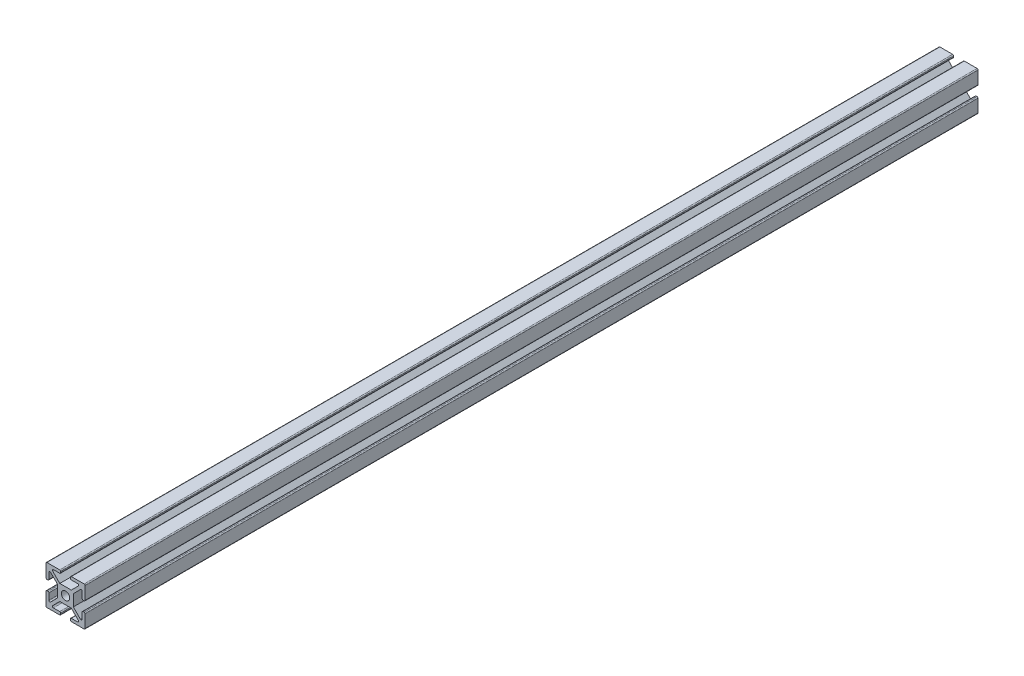
SolidWorks part; units mm, degrees
material "6061 Alloy"
ref_plane "Front Plane" through (0, 0, 0) normal (0, 0, 1) x (1, 0, 0)
ref_plane "Top Plane" through (0, 0, 0) normal (0, 1, 0) x (1, 0, 0)
ref_plane "Right Plane" through (0, 0, 0) normal (1, 0, 0) x (0, 0, -1)
sketch "Sketch1" plane through (0, 0, 0) normal (0, 0, 1) x (1, 0, 0)
  line L0 (-10, 2.5) -> (-8.5, 2.5)
  line L1 (-2.9393, 4) -> (0, 4)
  line L2 (-2.5, 10) -> (-10, 10)
  line L3 (-7.4393, 8.5) -> (-2.9393, 4)
  line L4 (-2.5, 8.5) -> (-7.4393, 8.5)
  line L5 (-8.5, 2.5) -> (-8.5, 7.4393)
  line L6 (-8.5, 7.4393) -> (-4, 2.9393)
  line L7 (-4, 2.9393) -> (-4, 0)
  line L8 (-4, 0) -> (-10, 0) construction
  line L9 (0, 10) -> (0, -10) construction
  line L10 (-10, 10) -> (0, 0) construction
  line L11 (-10, 2.5) -> (-10, 10)
  line L12 (-2.5, 10) -> (-2.5, 8.5)
  line L13 (-2.5, 10) -> (0, 10) construction
  line L14 (-10, 2.5) -> (-10, 0) construction
  line L15 (2.9393, 4) -> (0, 4)
  line L16 (4, 2.9393) -> (4, 0)
  line L17 (8.5, 7.4393) -> (4, 2.9393)
  line L18 (8.5, 2.5) -> (8.5, 7.4393)
  line L19 (10, 2.5) -> (8.5, 2.5)
  line L20 (10, 2.5) -> (10, 10)
  line L21 (2.5, 10) -> (10, 10)
  line L22 (2.5, 10) -> (2.5, 8.5)
  line L23 (2.5, 8.5) -> (7.4393, 8.5)
  line L24 (7.4393, 8.5) -> (2.9393, 4)
  line L25 (4, -2.9393) -> (4, 0)
  line L26 (2.9393, -4) -> (0, -4)
  line L27 (7.4393, -8.5) -> (2.9393, -4)
  line L28 (2.5, -8.5) -> (7.4393, -8.5)
  line L29 (2.5, -10) -> (2.5, -8.5)
  line L30 (2.5, -10) -> (10, -10)
  line L31 (10, -2.5) -> (10, -10)
  line L32 (10, -2.5) -> (8.5, -2.5)
  line L33 (8.5, -2.5) -> (8.5, -7.4393)
  line L34 (8.5, -7.4393) -> (4, -2.9393)
  line L35 (-2.9393, -4) -> (0, -4)
  line L36 (-4, -2.9393) -> (-4, 0)
  line L37 (-8.5, -7.4393) -> (-4, -2.9393)
  line L38 (-8.5, -2.5) -> (-8.5, -7.4393)
  line L39 (-10, -2.5) -> (-8.5, -2.5)
  line L40 (-10, -2.5) -> (-10, -10)
  line L41 (-2.5, -10) -> (-10, -10)
  line L42 (-2.5, -10) -> (-2.5, -8.5)
  line L43 (-2.5, -8.5) -> (-7.4393, -8.5)
  line L44 (-7.4393, -8.5) -> (-2.9393, -4)
  circle A0 centre (0, 0) radius 2.15
  point P53 (0, 0)
  dimension "D2" = 4.3
  dimension "D1" = 10
  dimension "D3" = 2.5
  dimension "D4" = 1.5
  dimension "D5" = 1.5
  dimension "D6" = 4
  dimension "D7" = 4
extrude "Boss-Extrude1" add sketch "Sketch1" along normal blind 457.2
fillet "Fillet1" radius 0.5 28 edges at (8.5, 2.5, 228.6) (2.5, 8.5, 228.6) (2.5, 10, 228.6) (2.5, -10, 228.6) (-10, 2.5, 228.6) (-8.5, -7.4393, 228.6) (-10, -10, 228.6) (-8.5, 7.4393, 228.6) (-7.4393, 8.5, 228.6) (7.4393, 8.5, 228.6) (8.5, -7.4393, 228.6) (7.4393, -8.5, 228.6) (-7.4393, -8.5, 228.6) (2.5, -8.5, 228.6) (-2.5, -10, 228.6) (-2.5, -8.5, 228.6) (10, -10, 228.6) (8.5, -2.5, 228.6) (10, -2.5, 228.6) (10, 2.5, 228.6) (-10, -2.5, 228.6) (-8.5, -2.5, 228.6) (-8.5, 2.5, 228.6) (-2.5, 8.5, 228.6) (-2.5, 10, 228.6) (-10, 10, 228.6) (10, 10, 228.6) (8.5, 7.4393, 228.6)
